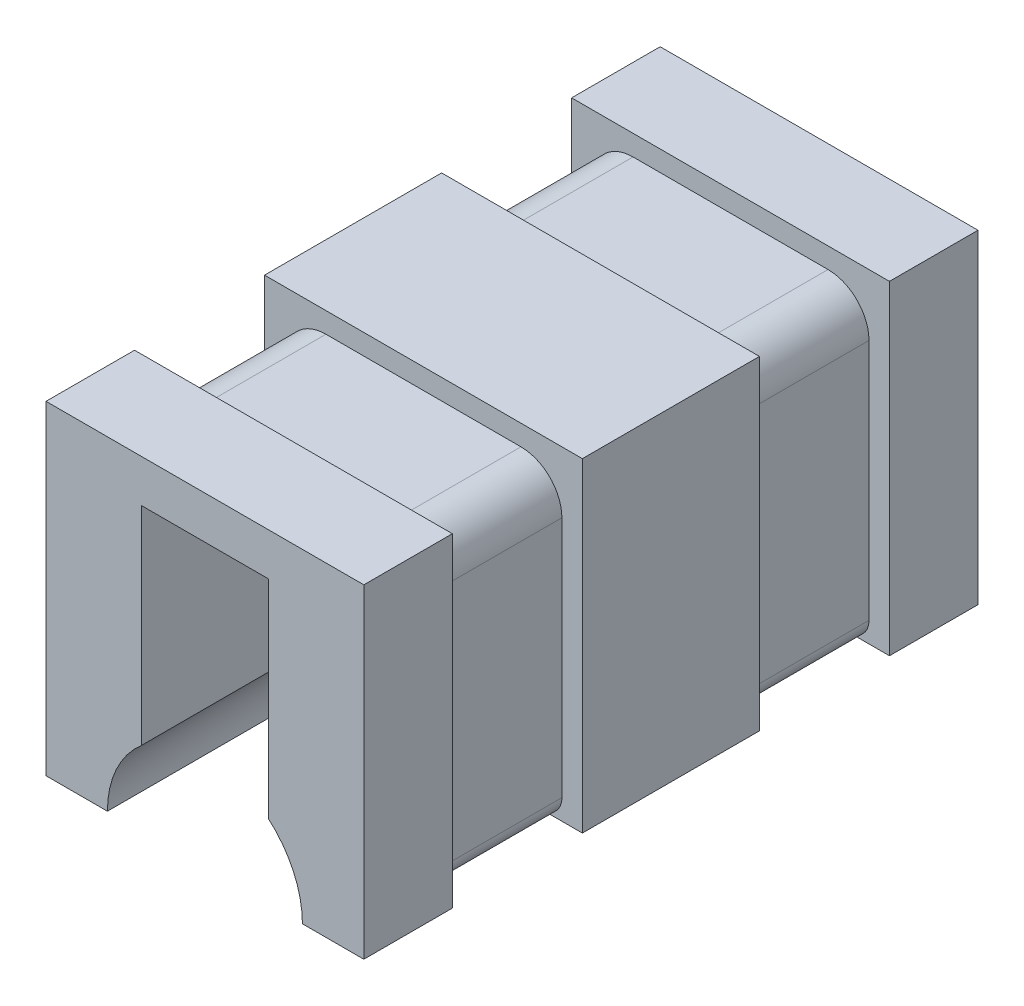
SolidWorks part; units mm, degrees
ref_plane "Front" through (0, 0, 0) normal (0, 0, 1) x (1, 0, 0)
ref_plane "Top" through (0, 0, 0) normal (0, 1, 0) x (1, 0, 0)
ref_plane "Right" through (0, 0, 0) normal (1, 0, 0) x (0, 0, -1)
sketch "Sketch1" plane through (0, 0, 0) normal (0, 0, 1) x (1, 0, 0)
  line L0 (-3.1, 3.6154) -> (-3.1, 13.7625)
  line L1 (3.1, 3.6154) -> (3.1, 13.7625)
  line L2 (4.7625, 0) -> (7.7625, 0)
  line L3 (7.7625, 0) -> (7.7625, 15.8405)
  line L4 (-7.7625, 15.8405) -> (7.7625, 15.8405)
  line L6 (-7.7625, 15.8405) -> (-7.7625, 0)
  line L7 (-7.7625, 0) -> (-4.7625, 0)
  line L8 (-3.1, 13.7625) -> (3.1, 13.7625)
  arc A0 (4.7625, 0) -> (3.1, 3.6154) centre (0, 0) ccw
  arc A1 (-3.1, 3.6154) -> (-4.7625, 0) centre (0, 0) ccw
  dimension "D1" = 9.525
  dimension "D2" = 6.2
  dimension "D3" = 13.7625
  dimension "D4" = 2.078
  dimension "D5" = 3
extrude "Boss-Extrude1" add sketch "Sketch1" along normal mid plane 30
ref_plane "Plane1" through (0, 0, 7.5) normal (0, 0, 1) x (1, 0, 0)
sketch "Sketch2" plane through (0, 0, 7.5) normal (0, 0, 1) x (1, 0, 0)
  line L1 (-7.7625, 15.8405) -> (-7.7625, 0) construction
  line L2 (7.7625, 15.8405) -> (-7.7625, 15.8405) construction
  line L4 (-7.7625, 15.8405) -> (-7.7625, 0)
  line L5 (0, 15.8405) -> (-7.7625, 15.8405)
  line L6 (-7.7625, 0) -> (-6.7625, 0)
  line L7 (-6.7625, 0) -> (-6.7625, 14.8405)
  line L10 (-6.7625, 14.8405) -> (0, 14.8405)
  line L11 (0, 14.8405) -> (0, 15.8405)
  dimension "D1" = 1
  dimension "D2" = 1
extrude "Cut-Extrude1" cut sketch "Sketch2" against normal mid plane 6.35
mirror "Mirror3" about plane through (0, 0, 0) normal (1, 0, 0) of "Cut-Extrude1"
mirror "Mirror4" about plane through (0, 0, 0) normal (0, 0, 1) of "Cut-Extrude1", "Mirror3"
fillet "Fillet1" radius 2 4 edges at (-6.7625, 14.8405, 7.5) (-6.7625, 14.8405, -7.5) (6.7625, 14.8405, -7.5) (6.7625, 14.8405, 7.5)
fillet "Fillet2" radius 1 4 edges at (-6.7625, 0, 7.5) (6.7625, 0, 7.5) (-6.7625, 0, -7.5) (6.7625, 0, -7.5)
